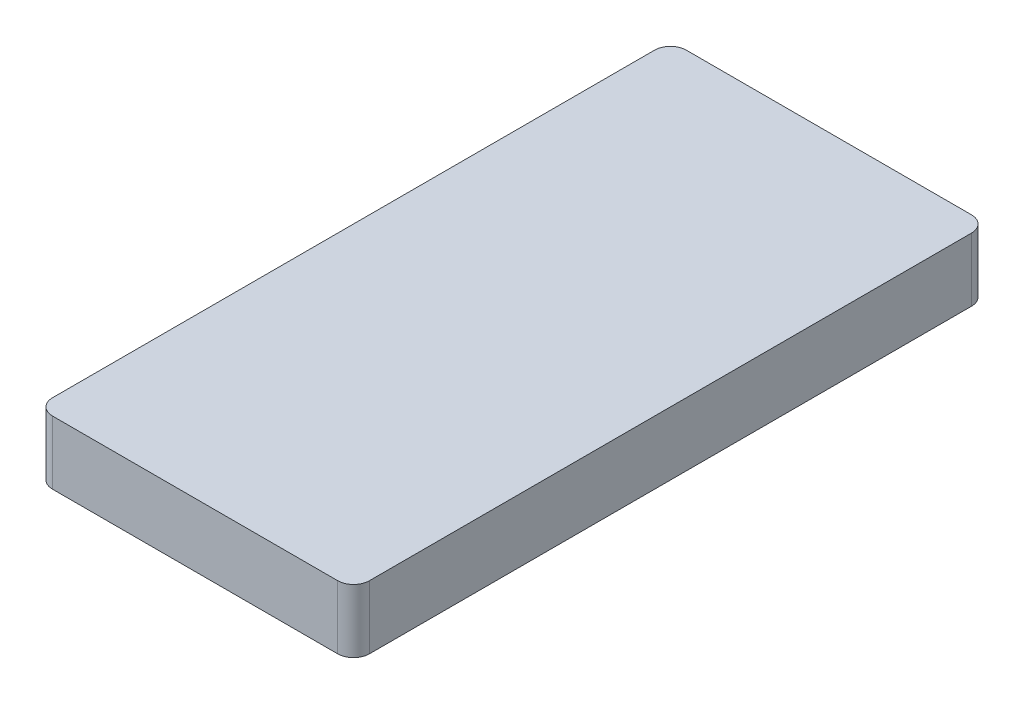
SolidWorks part; units mm, degrees
ref_plane "Front Plane" through (0, 0, 0) normal (0, 0, 1) x (1, 0, 0)
ref_plane "Top Plane" through (0, 0, 0) normal (0, 1, 0) x (1, 0, 0)
ref_plane "Right Plane" through (0, 0, 0) normal (1, 0, 0) x (0, 0, -1)
sketch "Sketch1" plane through (0, 0, 0) normal (0, 1, 0) x (1, 0, 0)
  line L1 (-5, -10) -> (5, -10)
  line L2 (-5, -10) -> (-5, 10)
  line L3 (-5, 10) -> (5, 10)
  line L4 (5, -10) -> (5, 10)
  line L5 (-5, -10) -> (5, 10) construction
  line L6 (-5, 10) -> (5, -10) construction
  point P0 (0, 0)
  dimension "D1" = 10
  dimension "D2" = 20
extrude "Boss-Extrude1" add sketch "Sketch1" along normal blind 2
fillet "Fillet1" radius 0.5 4 edges at (-5, 1, -10) (5, 1, -10) (-5, 1, 10) (5, 1, 10)
